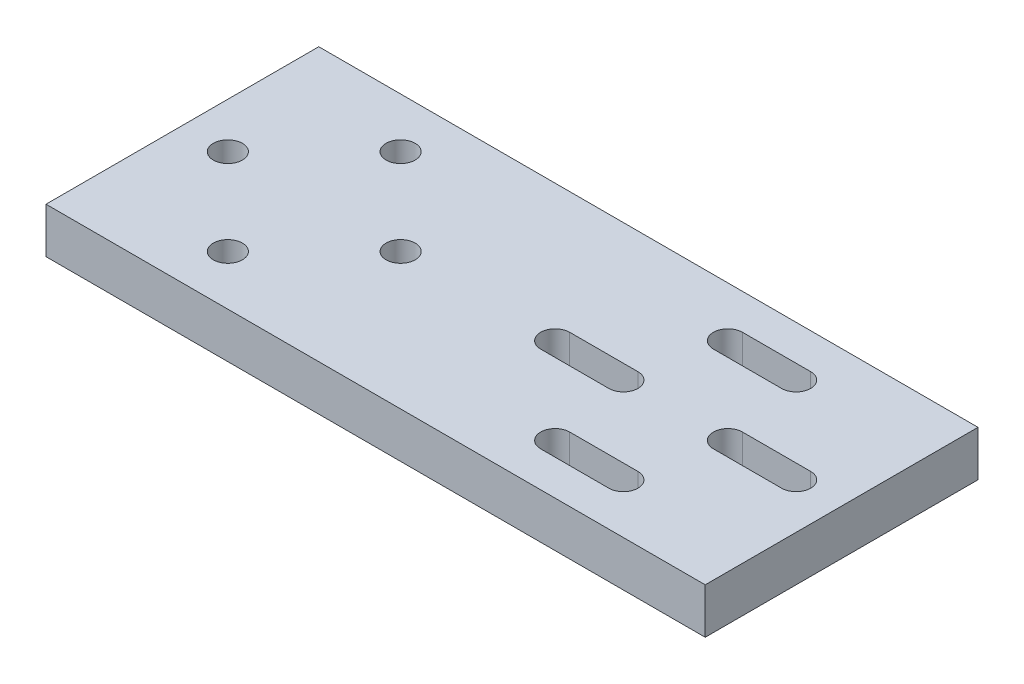
SolidWorks part; units mm, degrees
ref_plane "Front Plane" through (0, 0, 0) normal (0, 0, 1) x (1, 0, 0)
ref_plane "Top Plane" through (0, 0, 0) normal (0, 1, 0) x (1, 0, 0)
ref_plane "Right Plane" through (0, 0, 0) normal (1, 0, 0) x (0, 0, -1)
sketch "Sketch2" plane through (0, 0, 0) normal (0, 1, 0) x (1, 0, 0)
  line L1 (-32.5, 15) -> (32.5, 15)
  line L2 (-32.5, 15) -> (-32.5, -15)
  line L3 (-32.5, -15) -> (32.5, -15)
  line L4 (32.5, 15) -> (32.5, -15)
  line L5 (-32.5, 15) -> (32.5, -15) construction
  line L6 (-32.5, -15) -> (32.5, 15) construction
  point P0 (0, 0)
  dimension "D1" = 65
  dimension "D2" = 30
extrude "Boss-Extrude1" add sketch "Sketch2" along normal blind 5
sketch "Sketch3" plane through (0, 5, 0) normal (0, 1, 0) x (1, 0, 0)
  line L2 (0, 0) -> (0, 10.693) construction
  circle A0 centre (-27.5, 0) radius 1.6
  circle A8 centre (-18, 0) radius 16.7 construction
  circle A9 centre (-18, 9.5) radius 1.6
  circle A10 centre (-8.5, 0) radius 1.6
  circle A11 centre (-18, -9.5) radius 1.6
  circle A12 centre (18, -9.5) radius 1.6
  circle A13 centre (27.5, 0) radius 1.6
  circle A14 centre (18, 9.5) radius 1.6
  circle A15 centre (8.5, 0) radius 1.6
  dimension "D1" = 3.2
  dimension "D4" = 33.4
  dimension "D3" = 19
  dimension "D5" = 18
  dimension "D2" = 4
extrude "Cut-Extrude1" cut sketch "Sketch3" against normal through all
sketch "Sketch5" plane through (32.5, 0, 0) normal (1, 0, 0) x (0, 0, -1)
  line L4 (-15, 0) -> (15, 0)
  line L5 (15, 0) -> (15, 5)
  line L6 (15, 5) -> (-15, 5)
  line L7 (-15, 5) -> (-15, 0)
  line L8 (-15, 0) -> (15, 0)
  line L9 (15, 0) -> (15, 5)
  line L10 (15, 5) -> (-15, 5)
  line L11 (-15, 5) -> (-15, 0)
  dimension "D1" = 0
extrude "Boss-Extrude2" add sketch "Sketch5" along normal blind 7.5
sketch "Sketch4" plane through (0, 5, 0) normal (0, 1, 0) x (1, 0, 0)
  line L0 (8.5, 0) -> (16, 0) construction
  line L1 (8.5, 1.6) -> (16, 1.6)
  line L2 (8.5, -1.6) -> (16, -1.6)
  line L3 (27.5, 0) -> (35, 0) construction
  line L4 (27.5, 1.6) -> (35, 1.6)
  line L5 (27.5, -1.6) -> (35, -1.6)
  line L6 (18, -9.5) -> (25.5, -9.5) construction
  line L7 (18, -7.9) -> (25.5, -7.9)
  line L8 (18, -11.1) -> (25.5, -11.1)
  line L9 (18, 9.5) -> (25.5, 9.5) construction
  line L10 (18, 11.1) -> (25.5, 11.1)
  line L11 (18, 7.9) -> (25.5, 7.9)
  arc A0 (8.5, 1.6) -> (8.5, -1.6) centre (8.5, 0) ccw
  arc A1 (16, -1.6) -> (16, 1.6) centre (16, 0) ccw
  arc A2 (27.5, 1.6) -> (27.5, -1.6) centre (27.5, 0) ccw
  arc A3 (35, -1.6) -> (35, 1.6) centre (35, 0) ccw
  arc A4 (18, -7.9) -> (18, -11.1) centre (18, -9.5) ccw
  arc A5 (25.5, -11.1) -> (25.5, -7.9) centre (25.5, -9.5) ccw
  arc A6 (18, 11.1) -> (18, 7.9) centre (18, 9.5) ccw
  arc A7 (25.5, 7.9) -> (25.5, 11.1) centre (25.5, 9.5) ccw
  circle A8 centre (27.5, 0) radius 1.6 construction
  point P4 (12.25, 0)
  point P9 (31.25, 0)
  point P17 (21.75, -9.5)
  point P25 (21.75, 9.5)
  dimension "D1" = 7.5
extrude "Cut-Extrude2" cut sketch "Sketch4" against normal blind 10
